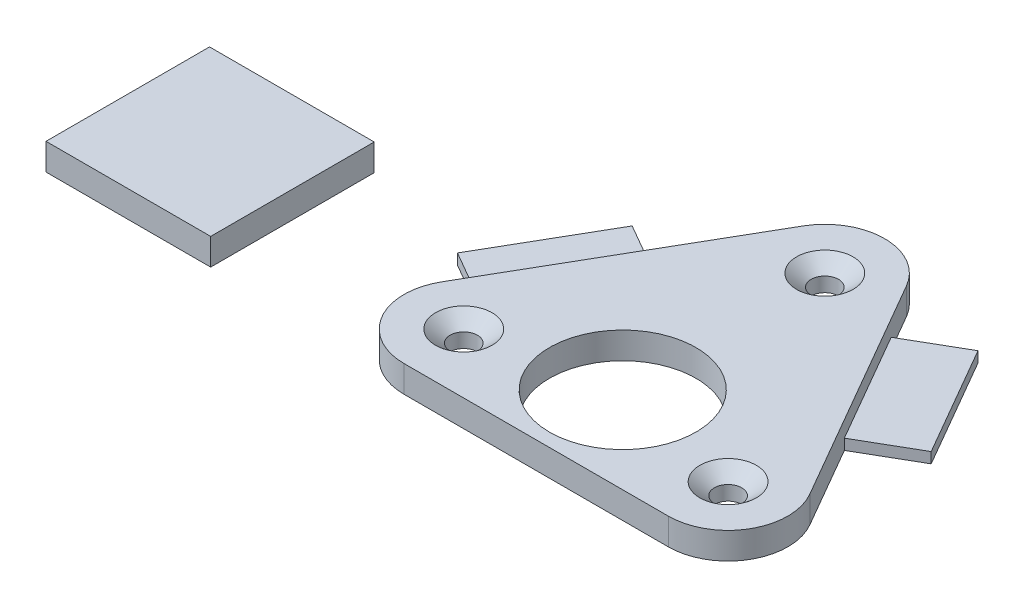
SolidWorks part; units mm, degrees
material "6061-T6 (SS)"
ref_plane "Front Plane" through (0, 0, 0) normal (0, 0, 1) x (1, 0, 0)
ref_plane "Top Plane" through (0, 0, 0) normal (0, 1, 0) x (1, 0, 0)
ref_plane "Right Plane" through (0, 0, 0) normal (1, 0, 0) x (0, 0, -1)
sketch "Sketch1" plane through (0, 0, 0) normal (0, 1, 0) x (1, 0, 0)
  line L0 (-6.1713, 27.6499) -> (-21.9212, 0.3703)
  line L1 (0, 5.9005) -> (0, 24.0869) construction
  line L4 (6.1713, 27.6499) -> (21.9212, 0.3703)
  line L6 (15.7499, -10.3187) -> (-15.7499, -10.3187)
  circle A0 centre (0, 0) radius 8.7312
  circle A2 centre (0, 24.0869) radius 1.4224 construction
  circle A9 centre (0, 5.9005) radius 21.4312 construction
  circle A10 centre (0, 5.9005) radius 14.9225 construction
  circle A11 centre (15.7499, -3.1927) radius 1.4224 construction
  circle A12 centre (-15.7499, -3.1927) radius 1.4224 construction
  arc A13 (-21.9212, 0.3703) -> (-15.7499, -10.3187) centre (-15.7499, -3.1927) ccw
  arc A14 (15.7499, -10.3187) -> (21.9212, 0.3703) centre (15.7499, -3.1927) ccw
  arc A15 (6.1713, 27.6499) -> (-6.1713, 27.6499) centre (0, 24.0869) ccw
  point P12 (0, 0)
  point P15 (0, 5.9005)
  dimension "D1" = 2.8448
  dimension "D2" = 17.4625
  dimension "D3" = 29.845
  dimension "D4" = 42.8625
  dimension "D8" = 10.3187
  dimension "D5" = 5.9005
  dimension "D6" = 3
  dimension "D7" = 18.1864
extrude "Boss-Extrude1" add sketch "Sketch1" along normal blind 3.175
hole_wizard "CSK for #4 Flat Head Machine Screw (100)1" positions "Sketch4" profile "Sketch5" countersink size "#4" standard "ANSI Inch" end condition through all
sketch "Sketch4" plane through (0, 3.175, 0) normal (0, 1, 0) x (1, 0, 0)
  point P0 (0, 24.0869)
  point P3 (-15.7499, -3.1927)
  point P6 (15.7499, -3.1927)
sketch "Sketch5" plane through (0, 3.175, -24.0869) normal (1, 0, 0) x (0, 0, 1)
  line L0 (0, 0) -> (0, 3.175)
  line L1 (0, 3.175) -> (1.6319, 3.175)
  line L2 (1.6319, 3.175) -> (1.6319, 1.4546)
  line L3 (1.6319, 1.4546) -> (3.3655, 0)
  line L5 (3.3655, 0) -> (0, 0)
  line L6 (-1.632, 1.4546) -> (-3.3655, 0) construction
  line L11 (0, -6.35) -> (0, 107.95) construction
  dimension "Thru Hole Dia." = 3.2639
  dimension "Thru Hole Depth" = 3.175
  dimension "Near C'Sink Dia." = 6.731
  dimension "Near C'Sink Angle" = 100
sketch "Sketch6" plane through (0, 3.175, 0) normal (0, 1, 0) x (1, 0, 0)
  line L1 (-40.3863, -8.717) -> (-60.011, -8.717)
  line L2 (-40.3863, -8.717) -> (-40.3863, 10.7712)
  line L3 (-40.3863, 10.7712) -> (-60.011, 10.7712)
  line L4 (-60.011, -8.717) -> (-60.011, 10.7712)
  line L5 (-40.3863, -8.717) -> (-60.011, 10.7712) construction
  line L6 (-40.3863, 10.7712) -> (-60.011, -8.717) construction
  point P4 (-50.1987, 1.0271)
extrude "Boss-Extrude2" add sketch "Sketch6" against normal up to surface (3.175 mm away) separate body up to face at (0, 0, -22.4549)
sketch "Sketch7" plane through (0, 0, 0) normal (0, -1, 0) x (1, 0, 0)
  line L0 (16.2892, -10.1252) -> (8.6692, -23.3234)
  line L1 (16.2892, -10.1252) -> (22.8492, -13.9126)
  line L2 (8.6692, -23.3234) -> (15.2292, -27.1108)
  line L3 (22.8492, -13.9126) -> (15.2292, -27.1108)
  line L4 (21.9212, -0.3703) -> (6.1713, -27.6499) construction
  line L5 (-12.7725, -16.2164) -> (-20.3925, -3.0181)
  line L6 (-12.7725, -16.2164) -> (-18.2555, -19.382)
  line L7 (-20.3925, -3.0181) -> (-25.8755, -6.1838)
  line L8 (-18.2555, -19.382) -> (-25.8755, -6.1838)
  line L9 (-6.1713, -27.6499) -> (-21.9212, -0.3703) construction
  dimension "D1" = 15.24
extrude "Boss-Extrude3" add sketch "Sketch7" against normal blind 1.27
